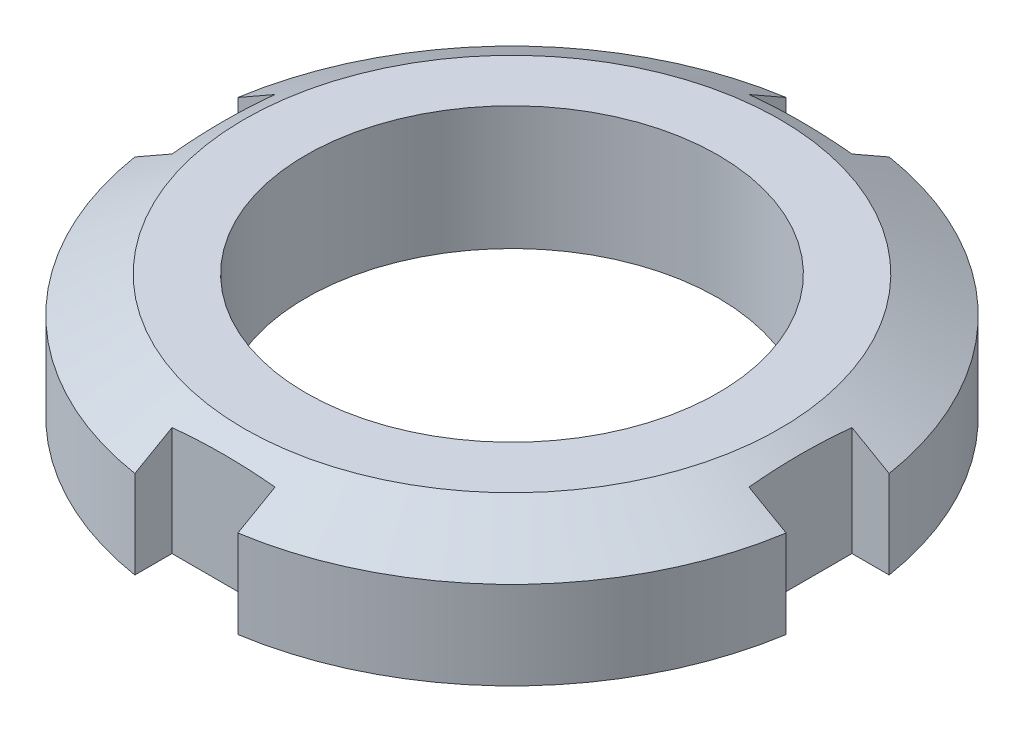
SolidWorks part; units mm, degrees
ref_plane "Alzado" through (0, 0, 0) normal (0, 0, 1) x (1, 0, 0)
ref_plane "Planta" through (0, 0, 0) normal (0, 1, 0) x (1, 0, 0)
ref_plane "Vista lateral" through (0, 0, 0) normal (1, 0, 0) x (0, 0, -1)
sketch "Croquis1" plane through (0, 0, 0) normal (0, 1, 0) x (1, 0, 0)
  circle A0 centre (0, 0) radius 10
  circle A1 centre (0, 0) radius 16
  dimension "D1" = 20
  dimension "D2" = 32
extrude "Saliente-Extruir1" add sketch "Croquis1" along normal blind 6
sketch "Croquis2" plane through (0, 6, 0) normal (0, 1, 0) x (1, 0, 0)
  line L1 (-2.5, 16) -> (2.5, 16)
  line L2 (-2.5, 16) -> (-2.5, 14)
  line L3 (-2.5, 14) -> (2.5, 14)
  line L4 (2.5, 16) -> (2.5, 14)
  line L5 (-2.5, -14) -> (2.5, -14)
  line L6 (-2.5, -14) -> (-2.5, -16)
  line L7 (-2.5, -16) -> (2.5, -16)
  line L8 (2.5, -14) -> (2.5, -16)
  line L9 (14, 2.5) -> (16, 2.5)
  line L10 (14, 2.5) -> (14, -2.5)
  line L11 (14, -2.5) -> (16, -2.5)
  line L12 (16, 2.5) -> (16, -2.5)
  line L13 (-14, -2.5) -> (-16, -2.5)
  line L14 (-14, -2.5) -> (-14, 2.5)
  line L15 (-14, 2.5) -> (-16, 2.5)
  line L16 (-16, -2.5) -> (-16, 2.5)
  dimension "D1" = 2.5
  dimension "D2" = 2.5
  dimension "D3" = 2
  dimension "D4" = 16
  dimension "D5" = 2
  dimension "D6" = 16
  dimension "D7" = 2.5
  dimension "D8" = 2.5
  dimension "D9" = 2
  dimension "D10" = 16
  dimension "D11" = 2.5
  dimension "D12" = 2.5
  dimension "D13" = 2.5
  dimension "D14" = 2.5
  dimension "D15" = 2
  dimension "D16" = 16
extrude "Cortar-Extruir1" cut sketch "Croquis2" against normal blind 6
sketch "Croquis3" plane through (0, 0, 0) normal (1, 0, 0) x (0, 0, -1)
  line L0 (-16, 6) -> (-13, 6)
  line L1 (-2.5, 6) -> (-15.8035, 6) construction
  line L2 (-13, 6) -> (-16, 4.2679)
  line L4 (-16, 4.2679) -> (-16, 6)
  dimension "D1" = 30
  dimension "D2" = 3
  dimension "D3" = 16
revolve "Cortar-Revolución1" cut sketch "Croquis3" angle 360 about axis through (0, 6, 0) along (0, -1, 0)
